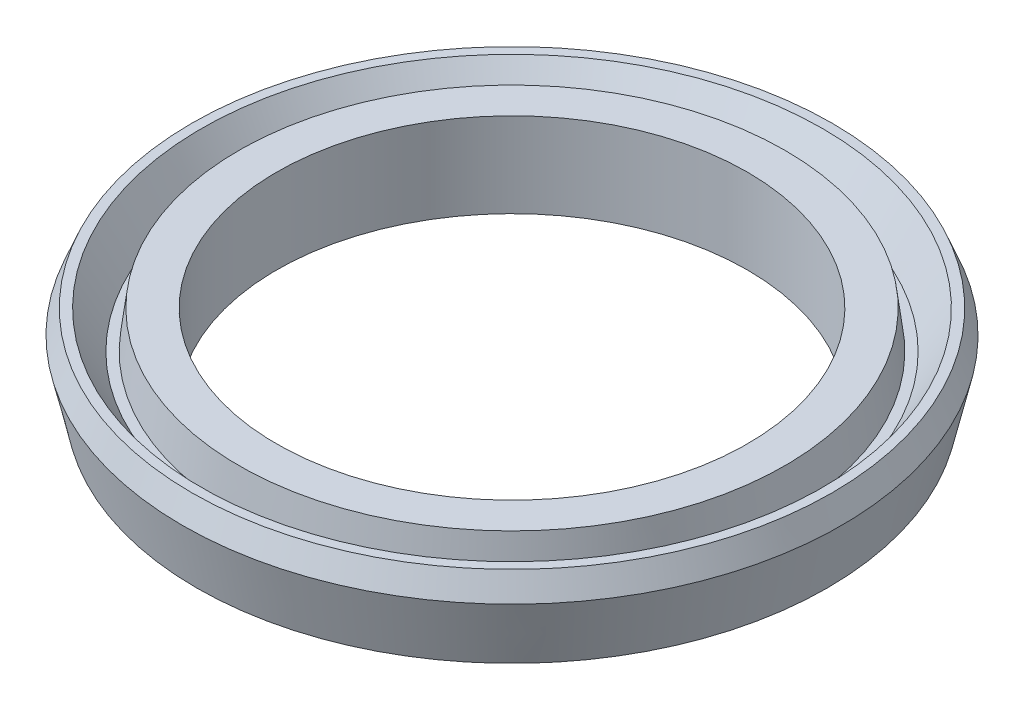
SolidWorks part; units mm, degrees
material "Silicon Rubber"
ref_plane "Front Plane" through (0, 0, 0) normal (0, 0, 1) x (1, 0, 0)
ref_plane "Top Plane" through (0, 0, 0) normal (0, 1, 0) x (1, 0, 0)
ref_plane "Right Plane" through (0, 0, 0) normal (1, 0, 0) x (0, 0, -1)
sketch "SealProfileS" plane through (0, 0, 0) normal (0, 0, 1) x (1, 0, 0)
  line L0 (5, 0) -> (5, 1.8)
  line L1 (5, 1.8) -> (5.8, 1.8)
  line L2 (5.8, 1.8) -> (5.9, 1)
  line L3 (5.9, 1) -> (6.1, 1)
  line L4 (6.1, 1) -> (6.6, 1.8)
  line L5 (6.6, 1.8) -> (6.8, 1.8)
  line L6 (6.8, 1.8) -> (7, 1.3)
  line L7 (7, 1.3) -> (6.7, 0)
  line L9 (6.7, 0) -> (5, 0)
  line L10 (0, 0) -> (0, 1.8) construction
  line L11 (0, 0) -> (5, 0) construction
  point P13 (7, 0.0813)
  dimension "ID" = 10
  dimension "Height" = 1.8
  dimension "OuterChamferHeight" = 0.5
  dimension "InnerThickness" = 0.8
  dimension "OuterThickness" = 0.2
  dimension "RefDia" = 14
  dimension "InnerGrooveWidth" = 0.2
  dimension "GrooveDraftLeft" = 0.1
  dimension "GrooveDraftRight" = 0.5
  dimension "InnerGrooveHeight" = 0.8
  dimension "XDimBottomDia" = 0.3
  dimension "XDimTopDia" = 0.2
revolve "SealProfile" add sketch "SealProfileS" angle 360 about L10
